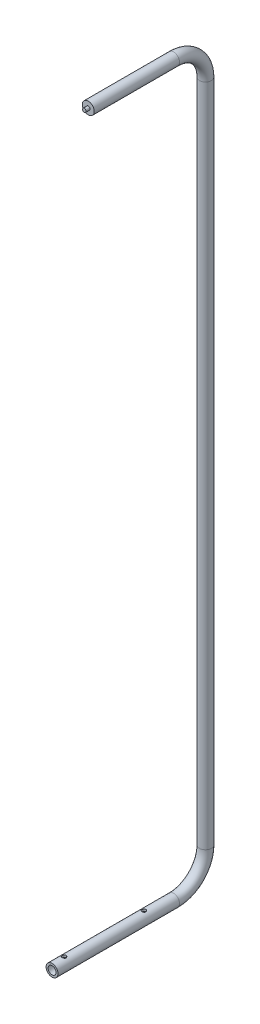
SolidWorks part; units mm, degrees
ref_plane "Front Plane" through (0, 0, 0) normal (0, 0, 1) x (1, 0, 0)
ref_plane "Top Plane" through (0, 0, 0) normal (0, 1, 0) x (1, 0, 0)
ref_plane "Right Plane" through (0, 0, 0) normal (1, 0, 0) x (0, 0, -1)
sketch "Sketch1" plane through (0, 0, 0) normal (1, 0, 0) x (0, 0, -1)
  line L0 (0, 1828.2) -> (0, 0) construction
  line L2 (0, 0) -> (304.8, 0)
  line L3 (0, 1828.2) -> (304.8, 1828.2)
  line L4 (384.8, 80) -> (384.8, 1748.2)
  arc A0 (304.8, 0) -> (384.8, 80) centre (304.8, 80) ccw
  arc A1 (304.8, 1828.2) -> (384.8, 1748.2) centre (304.8, 1748.2) cw
  point P3 (0, 1828.2)
  dimension "D3" = 304.8
  dimension "D5" = 80
  dimension "D6" = 80
  dimension "D1" = 384.8
  dimension "D2" = 1828.2
  dimension "D4" = 304.8
  dimension "D7" = 1668.2
sketch "Sketch2" plane through (0, 0, 0) normal (0, 0, 1) x (1, 0, 0)
  line L0 (0, 1748.2) -> (0, 1828.2) construction
  line L1 (0, 1828.2) -> (0, 0) construction
  circle A0 centre (0, 1828.2) radius 15
  circle A1 centre (0, 1828.2) radius 10
  dimension "D1" = 20
  dimension "D2" = 30
sweep "Sweep2" add profiles "Sketch2" path "Sketch1"
sketch "Sketch5" plane through (0, 0, 0) normal (0, 1, 0) x (1, 0, 0)
  line L0 (0, 436.0695) -> (0, 0) construction
  circle A0 centre (0, 30) radius 5
  circle A1 centre (0, 230) radius 5
  point P7 (0, 0)
  dimension "D2" = 10
  dimension "D4" = 10
  dimension "D1" = 30
  dimension "D3" = 200
extrude "Cut-Extrude2" cut sketch "Sketch5" against normal mid plane 317
sketch "Sketch6" plane through (0, 0, 0) normal (0, 0, 1) x (1, 0, 0)
  circle A0 centre (0, 1828.2) radius 30
  dimension "D1" = 60
extrude "Cut-Extrude3" cut sketch "Sketch6" against normal blind 90.8
sketch "Sketch9" plane through (0, 0, -90.8) normal (0, 0, 1) x (1, 0, 0)
  circle A0 centre (0, 1828.2) radius 10
extrude "Boss-Extrude2" add sketch "Sketch9" against normal blind 211.8
sketch "Sketch10" plane through (0, 0, -90.8) normal (0, 0, 1) x (1, 0, 0)
  circle A0 centre (0, 1828.2) radius 4.5
extrude "Boss-Extrude3" add sketch "Sketch10" along normal blind 10 contours A0
